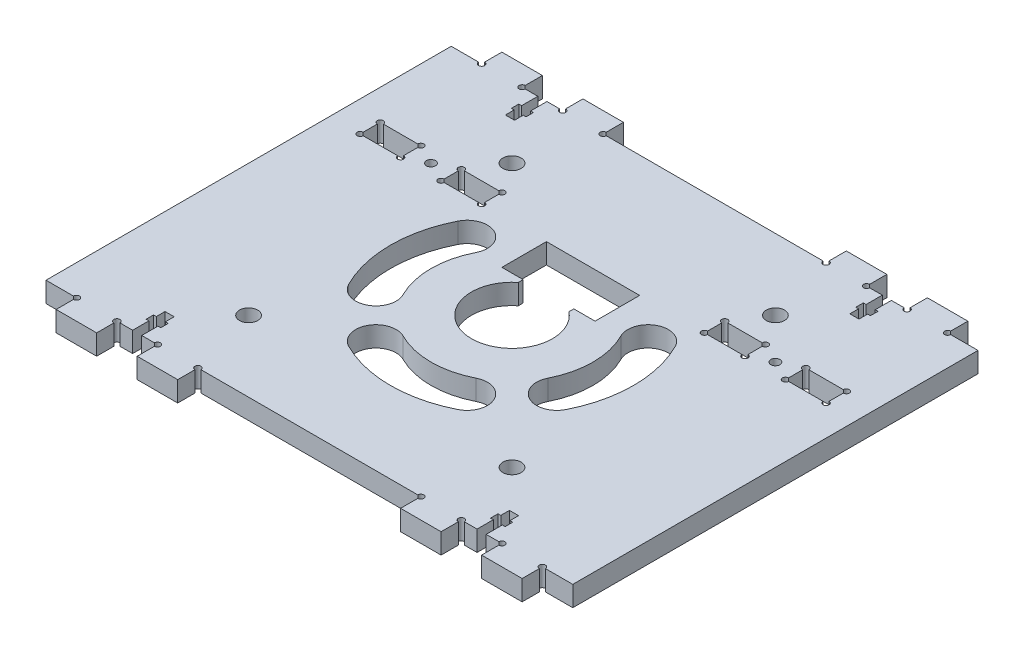
SolidWorks part; units mm, degrees
material "POLICARB. TRANSP."
ref_plane "Front Plane" through (0, 0, 0) normal (0, 0, 1) x (1, 0, 0)
ref_plane "Top Plane" through (0, 0, 0) normal (0, 1, 0) x (1, 0, 0)
ref_plane "Right Plane" through (0, 0, 0) normal (1, 0, 0) x (0, 0, -1)
sketch "Sketch1" plane through (0, 0, 0) normal (0, 1, 0) x (1, 0, 0)
  line L1 (130, 100) -> (-130, 100)
  line L2 (130, 100) -> (130, -100)
  line L3 (130, -100) -> (-130, -100)
  line L4 (-130, 100) -> (-130, -100)
  line L5 (0, -100) -> (0, 100) construction
  line L6 (130, 0) -> (-130, 0) construction
  point P0 (0, 0)
  dimension "D1" = 200
  dimension "D2" = 260
extrude "Extrude1" add sketch "Sketch1" along normal blind 10
sketch "Sketch3" plane through (0, 10, 0) normal (0, 1, 0) x (1, 0, 0)
  line L0 (130, 100) -> (-130, 100) construction
  line L1 (-115, 50) -> (-95, 50)
  line L2 (-115, 50) -> (-115, 40)
  line L3 (-115, 40) -> (-95, 40)
  line L4 (-95, 50) -> (-95, 40)
  line L9 (95, 50) -> (115, 50)
  line L10 (95, 50) -> (95, 40)
  line L11 (95, 40) -> (115, 40)
  line L12 (115, 50) -> (115, 40)
  line L13 (0, 0) -> (0, -100) construction
  line L14 (-130, -100) -> (130, -100) construction
  line L15 (-130, 100) -> (-130, -100) construction
  line L17 (-75, 50) -> (-55, 50)
  line L18 (-75, 50) -> (-75, 40)
  line L19 (-75, 40) -> (-55, 40)
  line L20 (-55, 50) -> (-55, 40)
  line L21 (55, 50) -> (75, 50)
  line L22 (55, 50) -> (55, 40)
  line L23 (55, 40) -> (75, 40)
  line L24 (75, 50) -> (75, 40)
  dimension "D1" = 50
  dimension "D2" = 20
  dimension "D3" = 10
  dimension "D4" = 15
  dimension "D5" = 20
  dimension "D6" = 10
  dimension "D7" = 20
extrude "Extrude2" cut sketch "Sketch3" against normal blind 10
hole_wizard "M4 Clearance Hole1" positions "Sketch4" profile "Sketch5" hole size "M4" standard "DIN" end condition through all
sketch "Sketch4" plane through (0, 10, 0) normal (0, 1, 0) x (1, 0, 0)
  line L0 (0, 0) -> (0, 100) construction
  line L8 (130, 100) -> (-130, 100) construction
  line L9 (-95, 45) -> (-75, 45) construction
  line L10 (-95, 40) -> (-95, 50) construction
  line L11 (-75, 50) -> (-75, 40) construction
  line L13 (-85, 45) -> (-85, 100) construction
  point P0 (-85, 45)
  point P2 (85, 45)
sketch "Sketch5" plane through (-85, 10, -45) normal (1, 0, 0) x (0, 0, 1)
  line L0 (0, 0) -> (0, 10)
  line L1 (0, 10) -> (2.25, 10)
  line L2 (2.25, 10) -> (2.25, 0)
  line L5 (2.25, 0) -> (0, 0)
  line L11 (0, -6.35) -> (0, 107.95) construction
  dimension "Thru Hole Dia." = 4.5
  dimension "Thru Hole Depth" = 10
sketch "Sketch6" plane through (0, 10, 0) normal (0, 1, 0) x (1, 0, 0)
  line L0 (-113.5, 50) -> (-115, 50)
  line L1 (-115, 50) -> (-115, 48.5)
  line L2 (-113.5, 40) -> (-115, 40)
  line L3 (-115, 40) -> (-115, 41.5)
  arc A0 (-115, 41.5) -> (-113.5, 40) centre (-115, 40) ccw
  arc A1 (-113.5, 50) -> (-115, 48.5) centre (-115, 50) ccw
  dimension "D1" = 3
extrude "Extrude3" cut sketch "Sketch6" against normal blind 10
ref_plane "Plane1" through (-105, 0, 0) normal (1, 0, 0) x (0, 0, -1)
mirror "Mirror1" about plane through (-105, 0, 0) normal (1, 0, 0) of "Extrude3"
ref_plane "Plane2" through (-85, 0, 0) normal (-1, 0, 0) x (0, 0, 1)
mirror "Mirror2" about plane through (-85, 0, 0) normal (-1, 0, 0) of "Mirror1", "Extrude3"
ref_plane "Plane3" through (0, 0, 0) normal (1, 0, 0) x (0, 0, -1)
mirror "Mirror3" about plane through (0, 0, 0) normal (1, 0, 0) of "Mirror2", "Mirror1", "Extrude3"
sketch "Sketch7" plane through (0, 10, 0) normal (0, 1, 0) x (1, 0, 0)
  line L0 (-130, -100) -> (130, -100) construction
  line L1 (-115, -100) -> (-95, -100)
  line L2 (-115, -100) -> (-115, -110)
  line L3 (-115, -110) -> (-95, -110)
  line L4 (-95, -100) -> (-95, -110)
  line L5 (-130, 100) -> (-130, -100) construction
  line L6 (-75, -100) -> (-55, -100)
  line L7 (-75, -100) -> (-75, -110)
  line L8 (-75, -110) -> (-55, -110)
  line L9 (-55, -100) -> (-55, -110)
  dimension "D1" = 20
  dimension "D2" = 15
  dimension "D3" = 20
  dimension "D4" = 10
extrude "Extrude4" add sketch "Sketch7" against normal blind 10
pattern_linear "LPattern1" count 2 spacing 170 along (1, 0, 0) count 2 spacing 210 along (0, 0, -1) of "Extrude4"
sketch "Sketch8" plane through (0, 10, 0) normal (0, 1, 0) x (1, 0, 0)
  line L0 (-116.5, -100) -> (-115, -100)
  line L1 (-115, -100) -> (-115, -101.5)
  line L3 (-95, -101.5) -> (-95, -100)
  line L4 (-95, -100) -> (-93.5, -100)
  line L5 (-75, -100) -> (-75, -101.5)
  line L7 (-55, -101.5) -> (-55, -100)
  line L8 (-55, -100) -> (-53.5, -100)
  line L9 (-55, -110) -> (-55, -100) construction
  line L10 (-76.5, -100) -> (-75, -100)
  arc A0 (-115, -101.5) -> (-116.5, -100) centre (-115, -100) ccw
  arc A1 (-93.5, -100) -> (-95, -101.5) centre (-95, -100) ccw
  arc A2 (-75, -101.5) -> (-76.5, -100) centre (-75, -100) ccw
  arc A3 (-53.5, -100) -> (-55, -101.5) centre (-55, -100) ccw
  dimension "D1" = 3
extrude "Extrude5" cut sketch "Sketch8" against normal blind 10
ref_plane "Plane4" through (0, 0, 0) normal (1, 0, 0) x (0, 0, -1)
ref_plane "Plane5" through (0, 0, 0) normal (0, 0, 1) x (1, 0, 0)
mirror "Mirror4" about plane through (0, 0, 0) normal (1, 0, 0) of "Extrude5"
mirror "Mirror5" about plane through (0, 0, 0) normal (0, 0, 1) of "Extrude5", "Mirror4"
sketch "Sketch9" plane through (0, 10, 0) normal (0, 1, 0) x (1, 0, 0)
  line L0 (-95, -105.75) -> (-75, -105.75) construction
  line L1 (-95, -110) -> (-95, -101.5) construction
  line L2 (-75, -101.5) -> (-75, -110) construction
  line L3 (-87.25, -100) -> (-87.25, -92)
  line L4 (-93.5, -100) -> (-76.5, -100) construction
  line L5 (-87.25, -92) -> (-88.625, -92)
  line L6 (-88.625, -92) -> (-88.625, -88.3)
  line L7 (-88.625, -88.3) -> (-87.25, -88.3)
  line L8 (-87.25, -88.3) -> (-87.25, -84)
  line L9 (-87.25, -84) -> (-82.75, -84)
  line L10 (-82.75, -84) -> (-82.75, -88.3)
  line L11 (-82.75, -88.3) -> (-81.375, -88.3)
  line L12 (-81.375, -88.3) -> (-81.375, -92)
  line L13 (-81.375, -92) -> (-82.75, -92)
  line L14 (-82.75, -92) -> (-82.75, -100)
  line L15 (-85, -105.75) -> (-85, -100) construction
  line L16 (-87.25, -100) -> (-82.75, -100)
  dimension "D1" = 16
  dimension "D2" = 8
  dimension "D3" = 4.5
  dimension "D4" = 7.25
  dimension "D5" = 3.7
extrude "Extrude6" cut sketch "Sketch9" against normal blind 10
mirror "Mirror6" about plane through (0, 0, 0) normal (1, 0, 0) of "Extrude6"
mirror "Mirror7" about plane through (0, 0, 0) normal (0, 0, 1) of "Mirror6", "Extrude6"
sketch "Sketch10" plane through (0, 10, 0) normal (0, 1, 0) x (1, 0, 0)
  line L0 (0, 0) -> (0, -100) construction
  line L1 (-23, 40) -> (23, 40)
  line L2 (-23, 40) -> (-23, 18)
  line L3 (-23, 18) -> (-12.5, 18)
  line L4 (23, 40) -> (23, 18)
  line L5 (-53.5, -100) -> (53.5, -100) construction
  line L6 (-12.5, 18) -> (-12.5, 15.6125)
  line L8 (12.5, 15.6125) -> (12.5, 18)
  line L9 (12.5, 18) -> (23, 18)
  arc A0 (-12.5, 15.6125) -> (12.5, 15.6125) centre (0, 0) ccw
  dimension "D1" = 40
  dimension "D2" = 46
  dimension "D3" = 22
  dimension "D4" = 40
  dimension "D5" = 25
extrude "Extrude7" cut sketch "Sketch10" against normal blind 10
sketch "Sketch11" plane through (0, 10, 0) normal (0, 1, 0) x (1, 0, 0)
  line L0 (0, 0) -> (0, -100) construction
  line L1 (-53.5, -100) -> (53.5, -100) construction
  line L2 (0, 0) -> (130, 0) construction
  line L3 (130, -100) -> (130, 100) construction
  arc A0 (44.6514, -22.5) -> (44.6514, 22.5) centre (0, 0) ccw construction
  arc A1 (53.5817, -27) -> (53.5817, 27) centre (0, 0) ccw
  arc A2 (35.7211, -18) -> (35.7211, 18) centre (0, 0) ccw
  arc A3 (35.7211, -18) -> (53.5817, -27) centre (44.6514, -22.5) ccw
  arc A4 (53.5817, 27) -> (35.7211, 18) centre (44.6514, 22.5) ccw
  arc A5 (22.5, -44.6514) -> (-22.5, -44.6514) centre (0, 0) cw construction
  arc A6 (-27, -53.5817) -> (27, -53.5817) centre (0, 0) ccw
  arc A7 (-18, -35.7211) -> (18, -35.7211) centre (0, 0) ccw
  arc A8 (-18, -35.7211) -> (-27, -53.5817) centre (-22.5, -44.6514) ccw
  arc A9 (27, -53.5817) -> (18, -35.7211) centre (22.5, -44.6514) ccw
  arc A10 (-44.6514, -22.5) -> (-44.6514, 22.5) centre (0, 0) cw construction
  arc A11 (-53.5817, 27) -> (-53.5817, -27) centre (0, 0) ccw
  arc A12 (-35.7211, 18) -> (-35.7211, -18) centre (0, 0) ccw
  arc A13 (-35.7211, 18) -> (-53.5817, 27) centre (-44.6514, 22.5) ccw
  arc A14 (-53.5817, -27) -> (-35.7211, -18) centre (-44.6514, -22.5) ccw
  point P4 (50, 0)
  point P9 (0, -50)
  point P18 (-50, 0)
  dimension "D1" = 45
  dimension "D3" = 10
  dimension "D4" = 50
  dimension "D5" = 50
  dimension "D6" = 50
  dimension "D2" = 45
extrude "Extrude8" cut sketch "Sketch11" against normal blind 10
hole_wizard "M8 Clearance Hole1" positions "Sketch12" profile "Sketch13" hole size "M8" standard "DIN" end condition through all
sketch "Sketch12" plane through (0, 10, 0) normal (0, 1, 0) x (1, 0, 0)
  line L0 (0, -100) -> (0, 0) construction
  line L1 (-53.5, -100) -> (53.5, -100) construction
  line L2 (0, 0) -> (130, 0) construction
  line L3 (130, -100) -> (130, 100) construction
  point P0 (-65, -65)
  point P2 (65, -65)
  point P4 (65, 65)
  point P6 (-65, 65)
  dimension "D1" = 130
  dimension "D2" = 130
sketch "Sketch13" plane through (-65, 10, 65) normal (1, 0, 0) x (0, 0, 1)
  line L0 (0, 0) -> (0, 10)
  line L1 (0, 10) -> (4.5, 10)
  line L2 (4.5, 10) -> (4.5, 0)
  line L5 (4.5, 0) -> (0, 0)
  line L11 (0, -6.35) -> (0, 107.95) construction
  dimension "Thru Hole Dia." = 9
  dimension "Thru Hole Depth" = 10
